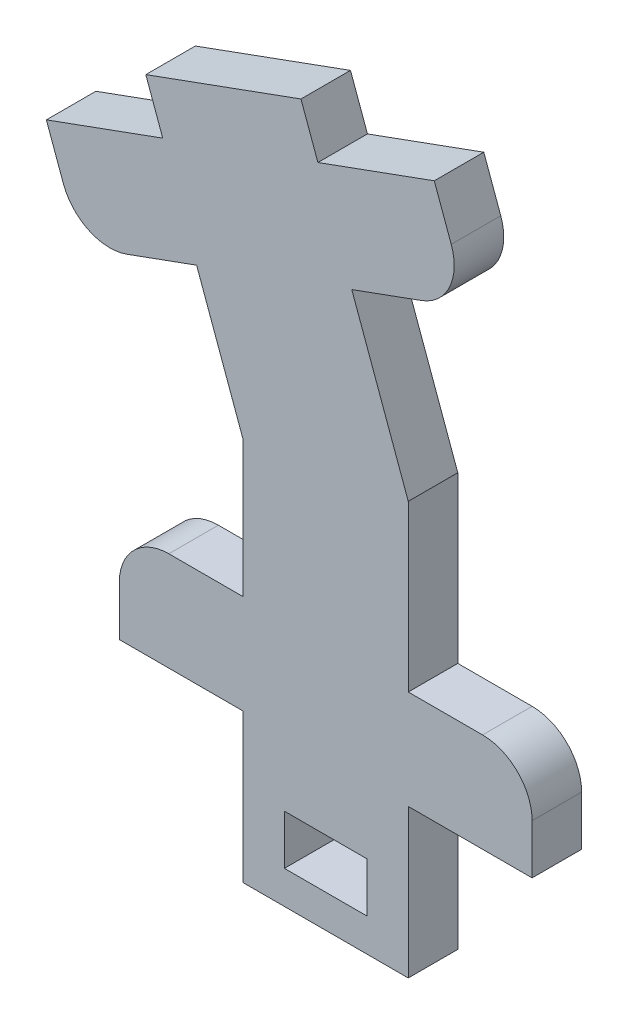
SolidWorks part; units mm, degrees
material "Maple"
ref_plane "Front Plane" through (0, 0, 0) normal (0, 0, 1) x (1, 0, 0)
ref_plane "Top Plane" through (0, 0, 0) normal (0, 1, 0) x (1, 0, 0)
ref_plane "Right Plane" through (0, 0, 0) normal (1, 0, 0) x (0, 0, -1)
sketch "Sketch1" plane through (0, 0, 0) normal (0, 0, 1) x (1, 0, 0)
  line L0 (0, -14.2367) -> (0, -23.2367)
  line L1 (0, -23.2367) -> (10, -23.2367)
  line L2 (10, -23.2367) -> (10, -14.2367)
  line L5 (10, 1.7633) -> (6.5798, 11.1602)
  line L6 (6.5798, 11.1602) -> (10.8084, 12.6993)
  line L7 (12.6014, 16.5444) -> (11.5754, 19.3635)
  line L8 (11.5754, 19.3635) -> (4.5277, 16.7984)
  line L9 (4.5277, 16.7984) -> (3.5016, 19.6174)
  line L10 (3.5016, 19.6174) -> (-5.8953, 16.1972)
  line L11 (-5.8953, 16.1972) -> (-4.8692, 13.3782)
  line L12 (-4.8692, 13.3782) -> (-11.9169, 10.813)
  line L13 (-11.9169, 10.813) -> (-10.8909, 7.9939)
  line L14 (-7.0457, 6.2009) -> (-2.8171, 7.74)
  line L15 (-2.8171, 7.74) -> (0, 0)
  line L16 (0, 0) -> (0, -8.2367)
  line L17 (0, -8.2367) -> (-4.5, -8.2367)
  line L18 (-7.5, -11.2367) -> (-7.5, -14.2367)
  line L19 (-7.5, -14.2367) -> (0, -14.2367)
  line L20 (10, 1.7633) -> (10, -8.2367)
  line L21 (10, -8.2367) -> (14.5, -8.2367)
  line L22 (17.5, -11.2367) -> (17.5, -14.2367)
  line L23 (10, -14.2367) -> (17.5, -14.2367)
  line L25 (2.5, -18.2367) -> (7.5, -18.2367)
  line L26 (2.5, -18.2367) -> (2.5, -21.2367)
  line L27 (2.5, -21.2367) -> (7.5, -21.2367)
  line L28 (7.5, -18.2367) -> (7.5, -21.2367)
  line L29 (2.5, -18.2367) -> (7.5, -21.2367) construction
  line L30 (2.5, -21.2367) -> (7.5, -18.2367) construction
  arc A0 (12.6014, 16.5444) -> (10.8084, 12.6993) centre (9.7824, 15.5184) cw
  arc A1 (-10.8909, 7.9939) -> (-7.0457, 6.2009) centre (-8.0718, 9.02) ccw
  arc A2 (17.5, -11.2367) -> (14.5, -8.2367) centre (14.5, -11.2367) ccw
  arc A3 (-7.5, -11.2367) -> (-4.5, -8.2367) centre (-4.5, -11.2367) cw
  point P5 (5, -19.7367)
  point P28 (0, 0)
  point P29 (5, -23.2367)
  point P34 (-9.8648, 5.1748)
  dimension "D13" = 3
  dimension "D1" = 160
  dimension "D2" = 10
  dimension "D3" = 10
  dimension "D4" = 10
  dimension "D5" = 10
  dimension "D6" = 6
  dimension "D7" = 25
  dimension "D8" = 3
  dimension "D9" = 9
  dimension "D10" = 5
  dimension "D11" = 2
  dimension "D12" = 3
extrude "Boss-Extrude1" add sketch "Sketch1" along normal blind 3
